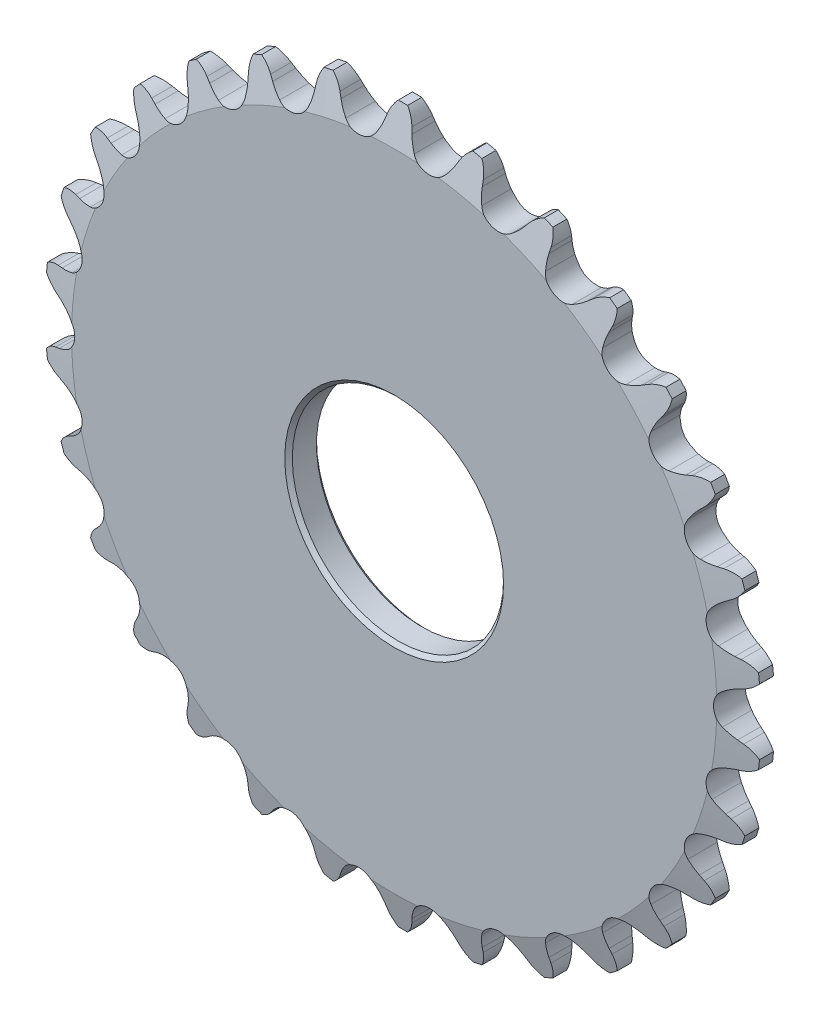
SolidWorks part; units mm, degrees
ref_plane "Front Plane" through (0, 0, 0) normal (0, 0, 1) x (1, 0, 0)
ref_plane "Top Plane" through (0, 0, 0) normal (0, 1, 0) x (1, 0, 0)
ref_plane "Right Plane" through (0, 0, 0) normal (1, 0, 0) x (0, 0, -1)
sketch "Sketch0" plane through (0, 0, 0) normal (0, 0, 1) x (1, 0, 0)
  line L0 (4.7625, -45.3122) -> (0, 0) construction
  line L1 (0, 0) -> (14.0794, -43.3318) construction
  line L2 (0, 0) -> (-4.7625, -45.3122) construction
  line L3 (4.7625, -45.3122) -> (14.0794, -43.3318) construction
  line L4 (4.7625, -45.3122) -> (-4.7625, -45.3122) construction
  line L5 (8.041, -45.6968) -> (7.7268, -45.0764)
  line L6 (4.7625, -45.3122) -> (0, -45.8127) construction
  line L7 (1.6356, -46.37) -> (1.814, -45.6978)
  line L8 (0, -45.3122) -> (0, -48.1697) construction
  line L9 (6.6573, -43.5452) -> (1.7903, -48.0838) construction
  line L10 (0, 0) -> (0, -45.3122) construction
  line L11 (7.7268, -45.0764) -> (1.7903, -48.0838) construction
  line L12 (0, -48.1697) -> (0, -48.7003) construction
  line L13 (11.7191, -43.8335) -> (8.041, -45.6968) construction
  line L14 (-3.175, 13.9303) -> (-3.175, 17.1053)
  line L15 (-3.175, 17.1053) -> (3.175, 17.1053)
  line L16 (3.175, 17.1053) -> (3.175, 13.9303)
  line L17 (0, 0) -> (0, 17.1053) construction
  circle A0 centre (0, 0) radius 48.1697 construction
  circle A1 centre (0, 0) radius 45.5618 construction
  arc A2 (-2.563, -49.4297) -> (12.784, -47.8167) centre (0, 0) ccw
  circle A3 centre (0, 0) radius 48.7003 construction
  circle A4 centre (4.7625, -45.3122) radius 2.54 construction
  circle A5 centre (0, 0) radius 14.2875
  arc A7 (6.6573, -43.5452) -> (2.5418, -43.9778) centre (4.7625, -45.3122) ccw
  circle A8 centre (4.7625, -45.3122) radius 2.5908 construction
  arc A9 (8.041, -45.6968) -> (12.784, -47.8167) centre (11.7191, -43.8335) ccw
  arc A10 (7.7268, -45.0764) -> (6.6573, -43.5452) centre (1.7903, -48.0838) ccw
  arc A11 (1.6356, -46.37) -> (-2.563, -49.4297) centre (-2.3495, -45.3122) cw
  arc A12 (1.814, -45.6978) -> (2.5418, -43.9778) centre (8.246, -47.4053) cw
  point P18 (4.7625, -45.3122)
  point P32 (0, 48.1697)
  point P34 (-35.797, 32.2318)
  point P35 (-28.3134, 38.9701)
  point P36 (-19.5924, 44.0052)
  point P37 (10.015, 47.117)
  point P38 (19.5924, 44.0052)
  point P39 (28.3134, 38.9701)
  point P40 (35.797, 32.2318)
  point P41 (41.7161, 24.0848)
  point P42 (45.8121, 14.8852)
  point P43 (47.9058, 5.0351)
  point P44 (47.9058, -5.0351)
  point P45 (45.8121, -14.8852)
  point P46 (41.7161, -24.0848)
  point P47 (35.797, -32.2318)
  point P48 (28.3134, -38.9701)
  point P49 (19.5924, -44.0052)
  point P50 (10.015, -47.117)
  point P51 (0, -48.1697)
  point P52 (-10.015, -47.117)
  point P53 (-19.5924, -44.0052)
  point P54 (-28.3134, -38.9701)
  point P55 (-35.797, -32.2318)
  point P56 (-41.7161, -24.0848)
  point P57 (-45.8121, -14.8852)
  point P58 (-47.9058, -5.0351)
  point P59 (-47.9058, 5.0351)
  point P60 (-45.8121, 14.8852)
  point P61 (-41.7161, 24.0848)
  point P62 (-10.015, 47.117)
  point P96 (0, 0)
  dimension "D1" = 2.5908
  dimension "R" = 2.5908
  dimension "ID" = 28.575
  dimension "Keyway Width" = 6.35
  dimension "Keyway Depth" = 3.175
  dimension "Number of Teeth" = 30
sketch "Sketch15" plane through (0, 0, 0) normal (1, 0, 0) x (0, 0, -1)
  line L0 (-11.1125, 0) -> (11.1125, 0) construction
  line L1 (-11.1125, 14.2116) -> (-11.1125, 25.4)
  line L2 (-11.1125, 25.4) -> (6.8453, 25.4)
  line L3 (6.8453, 25.4) -> (6.8453, 48.133)
  line L4 (6.8453, 48.133) -> (11.1125, 48.133)
  line L5 (11.1125, 48.133) -> (11.1125, 14.2116)
  line L7 (0, 14.2875) -> (0, -14.2875) construction
  line L8 (0, 9.9219) -> (0, -9.9219) construction
  line L9 (-11.1125, 14.2116) -> (-11.1125, 9.9219)
  line L10 (-11.1125, 9.9219) -> (11.1125, 9.9219)
  line L11 (11.1125, 9.9219) -> (11.1125, 14.2116)
  point P10 (8.9789, 48.133)
  point P12 (0, 0)
  point P15 (0, 0)
  point P16 (0, 0)
  point P17 (0, 5.0516)
  point P19 (0, -7.174)
  point P21 (0, 0)
  dimension "t" = 4.2672
  dimension "Overall Width" = 22.225
  dimension "OD" = 96.266
  dimension "Hub Diameter" = 50.8
  dimension "D1" = 19.8438
sketch "Sketch1" plane through (0, 0, 0) normal (1, 0, 0) x (0, 0, -1)
  line L0 (11.1125, 0) -> (6.8453, 0)
  line L1 (6.8453, 0) -> (6.8453, 43.4072)
  line L2 (6.8453, 43.4072) -> (8.0359, 48.1697)
  line L3 (8.0359, 48.1697) -> (9.9219, 48.1697)
  line L4 (9.9219, 48.1697) -> (11.1125, 43.4072)
  line L5 (11.1125, 43.4072) -> (11.1125, 0)
  line L7 (0, 48.1697) -> (0, -48.1697) construction
  line L8 (6.8453, 43.4072) -> (11.1125, 43.4072) construction
  line L9 (0, 48.1697) -> (0, -48.1697) construction
  line L10 (6.8453, 43.4072) -> (6.8453, 48.1697) construction
  line L11 (6.8453, 48.1697) -> (8.0359, 48.1697) construction
  line L12 (9.9219, 48.1697) -> (11.1125, 48.1697) construction
  line L13 (11.1125, 48.1697) -> (11.1125, 43.4072) construction
  line L15 (-11.1125, 0) -> (11.1125, 0) construction
  line L17 (11.1125, 48.133) -> (11.1125, 14.2116) construction
  line L22 (11.1125, 0) -> (-11.1125, 0) construction
  line L24 (6.8453, 0) -> (6.8453, 34.0792) construction
sketch "Sketch16" plane through (0, 0, 0) normal (1, 0, 0) x (0, 0, -1)
  line L1 (6.8453, 14.2116) -> (11.1125, 14.2116)
  line L3 (6.8453, 25.4) -> (6.8453, 43.4072)
  line L4 (6.8453, 43.4072) -> (8.0359, 48.1697)
  line L5 (8.0359, 48.1697) -> (9.9219, 48.1697)
  line L6 (9.9219, 48.1697) -> (11.1125, 43.4072)
  line L7 (11.1125, 43.4072) -> (11.1125, 14.2116)
  line L8 (6.8453, 25.4) -> (6.8453, 14.2116)
revolve "Revolve3" add sketch "Sketch16" angle 360 about L0
sketch "Sketch18" plane through (0, 0, -11.1125) normal (0, 0, -1) x (-1, 0, 0)
  line L0 (-1.6356, -46.37) -> (-1.814, -45.6978) construction
  line L1 (-8.041, -45.6968) -> (-7.7268, -45.0764) construction
  line L2 (-1.6356, -46.37) -> (-1.814, -45.6978)
  line L3 (-8.041, -45.6968) -> (-7.7268, -45.0764)
  arc A0 (-1.814, -45.6978) -> (-2.5418, -43.9778) centre (-8.246, -47.4053) ccw construction
  arc A1 (-2.5418, -43.9778) -> (-6.6573, -43.5452) centre (-4.7625, -45.3122) ccw construction
  arc A2 (-6.6573, -43.5452) -> (-7.7268, -45.0764) centre (-1.7903, -48.0838) ccw construction
  arc A3 (-12.784, -47.8167) -> (-8.041, -45.6968) centre (-11.7191, -43.8335) ccw construction
  arc A4 (-12.784, -47.8167) -> (2.563, -49.4297) centre (0, 0) ccw construction
  arc A5 (-1.6356, -46.37) -> (2.563, -49.4297) centre (2.3495, -45.3122) ccw construction
  arc A6 (-1.814, -45.6978) -> (-2.5418, -43.9778) centre (-8.246, -47.4053) ccw
  arc A7 (-2.5418, -43.9778) -> (-6.6573, -43.5452) centre (-4.7625, -45.3122) ccw
  arc A8 (-6.6573, -43.5452) -> (-7.7268, -45.0764) centre (-1.7903, -48.0838) ccw
  arc A9 (-12.784, -47.8167) -> (-8.041, -45.6968) centre (-11.7191, -43.8335) ccw
  arc A10 (-12.784, -47.8167) -> (2.563, -49.4297) centre (0, 0) ccw
  arc A11 (-1.6356, -46.37) -> (2.563, -49.4297) centre (2.3495, -45.3122) ccw
extrude "Cut-Extrude8" cut sketch "Sketch18" against normal up to next
pattern_circular "CirPattern1" count 30 over 360 about axis through (0, 0, 0) along (0, 0, 1) of "Cut-Extrude8"
chamfer "Chaflán2" distance 0.508 angle 45 2 edges at (14.2116, 0, -6.8453) (14.2116, 0, -11.1125)
equation "\"360/N@Sketch0\" = 360 / \"Number of Teeth@Sketch0\""
equation "\"Ds@Sketch0\" = 1.005 * \"Dr@Sketch0\" + 0.003"
equation "\"R@Sketch0\" = 1/2 * \"Ds@Sketch0\""
equation "\"A@Sketch0\" = 35 +  ( 60 / \"Number of Teeth@Sketch0\" ) "
equation "\"B@Sketch0\" = 18 -  ( 56 / \"Number of Teeth@Sketch0\" ) "
equation "\"ac@Sketch0\" = 0.8 * \"Dr@Sketch0\""
equation "\"ab@Sketch0\" = 1.4 * \"Dr@Sketch0\""
equation "\"J@Sketch0\" = 0.3 * \"Pitch@Sketch0\""
equation "\"h@Sketch1\" = \"Pitch@Sketch0\" / 2"
equation "\"g@Sketch1\" = \"h@Sketch1\" / 4"
equation "\"D3@Helix/Spiral1\"= \"Set Screw Pitch@Helix/Spiral1\" + ( \"Hub Diameter@Sketch15\" / 2 )"
equation "\"D1@Sketch6\" = \"Set Screw Pitch@Helix/Spiral1\" * 5 / 8"
equation "\"D2@Sketch6\" = \"Set Screw OD@Sketch6\" * 3 / 4"
equation "\"D1@Sketch8\" = \"Set Screw Pitch@Helix/Spiral1\" "
equation "\"D2@Sketch8\" = \"D1@Sketch8\" / 8"
equation "\"D1@Cut-Extrude6\" = \"Set Screw Hex@Sketch13\" * 5 / 8"
equation "\"D4@Helix/Spiral2\" = \"Set Screw Pitch@Helix/Spiral1\""
equation "\"D3@Helix/Spiral2\" = \"D4@Helix/Spiral2\" + \"Set Screw Lg.@Sketch10\""
equation "\"D1@CirPattern1\" = \"Number of Teeth@Sketch0\""
